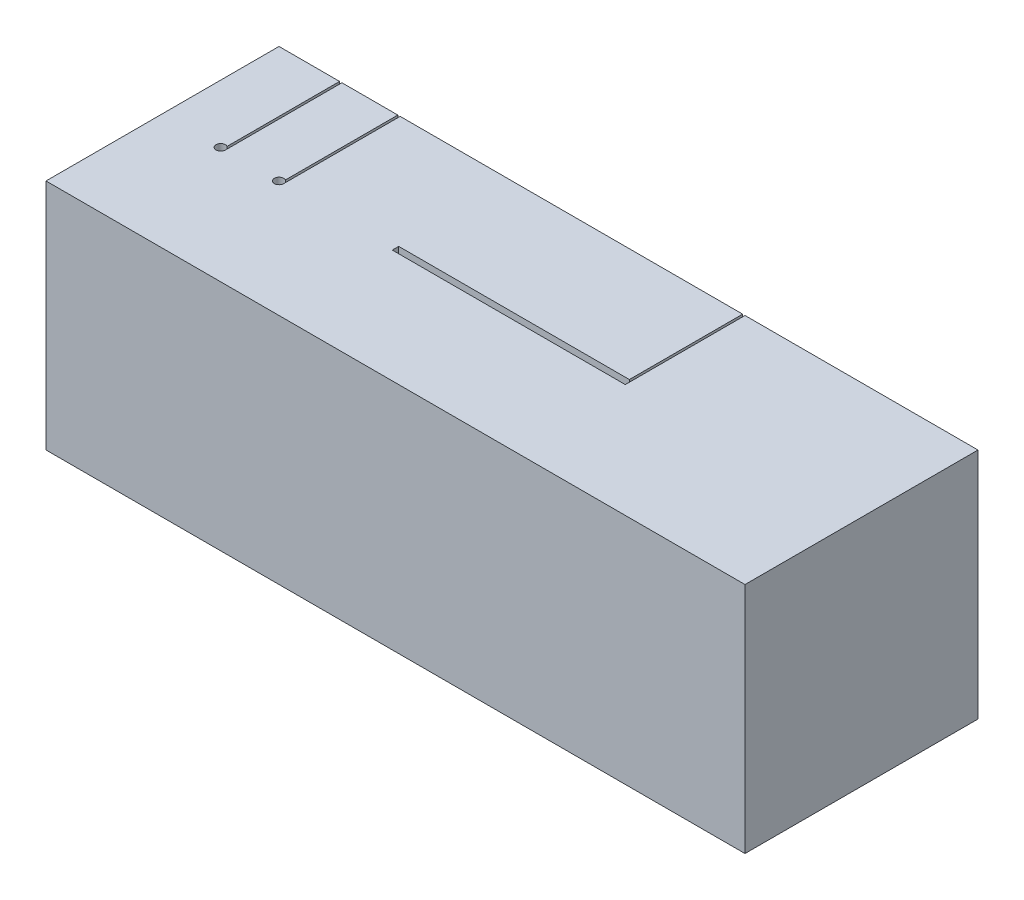
SolidWorks part; units mm, degrees
ref_plane "前视基准面" through (0, 0, 0) normal (0, 0, 1) x (1, 0, 0)
ref_plane "上视基准面" through (0, 0, 0) normal (0, 1, 0) x (1, 0, 0)
ref_plane "右视基准面" through (0, 0, 0) normal (1, 0, 0) x (0, 0, -1)
other "Configuration Table"
sketch "草图1" plane through (0, 0, 0) normal (0, 0, 1) x (1, 0, 0)
  line L1 (0, 0) -> (60, 0)
  line L2 (0, 0) -> (0, 20)
  line L3 (0, 20) -> (60, 20)
  line L4 (60, 0) -> (60, 20)
  dimension "D1" = 60
  dimension "D2" = 20
extrude "凸台-拉伸1" add sketch "草图1" along normal blind 20
sketch "草图2" plane through (0, 20, 0) normal (0, 1, 0) x (1, 0, 0)
  line L1 (20, -9.725) -> (40, -9.725)
  line L2 (20, -9.725) -> (20, -10.275)
  line L3 (20, -10.275) -> (40, -10.275)
  line L4 (40, -9.725) -> (40, -10.275)
  line L5 (60, 0) -> (0, 0) construction
  line L8 (60, -20) -> (60, 0) construction
  dimension "D1" = 0.55
  dimension "D2" = 9.725
  dimension "D3" = 20
  dimension "D4" = 20
extrude "切除-拉伸1" cut sketch "草图2" against normal through all
sketch "草图3" plane through (0, 20, 0) normal (0, 1, 0) x (1, 0, 0)
  line L0 (0, -20) -> (0, 0) construction
  line L1 (60, 0) -> (0, 0) construction
  circle A0 centre (5, -10) radius 0.4
  circle A1 centre (10, -10) radius 0.4
  dimension "D1" = 0.8
  dimension "D2" = 0.8
  dimension "D3" = 5
  dimension "D4" = 5
  dimension "D5" = 10
  dimension "D6" = 10
extrude "切除-拉伸2" cut sketch "草图3" against normal through all
sketch "草图4" plane through (0, 0, 0) normal (0, -1, 0) x (1, 0, 0)
  line L0 (0, 0) -> (60, 0) construction
  line L1 (5.4, 10) -> (5.2, 10)
  line L2 (5.4, 10) -> (5.4, 0)
  line L3 (5.4, 0) -> (5.2, 0)
  line L4 (5.2, 10) -> (5.2, 0)
  line L6 (10.4, 10) -> (10.2, 10)
  line L7 (10.4, 10) -> (10.4, 0)
  line L8 (10.4, 0) -> (10.2, 0)
  line L9 (10.2, 10) -> (10.2, 0)
  line L10 (40, 9.725) -> (39.8, 9.725)
  line L11 (40, 9.725) -> (40, 0)
  line L12 (40, 0) -> (39.8, 0)
  line L13 (39.8, 9.725) -> (39.8, 0)
  circle A0 centre (5, 10) radius 0.4 construction
  circle A1 centre (10, 10) radius 0.4 construction
  dimension "D1" = 0.2
  dimension "D2" = 0.2
  dimension "D3" = 0.2
extrude "切除-拉伸3" cut sketch "草图4" against normal through all
